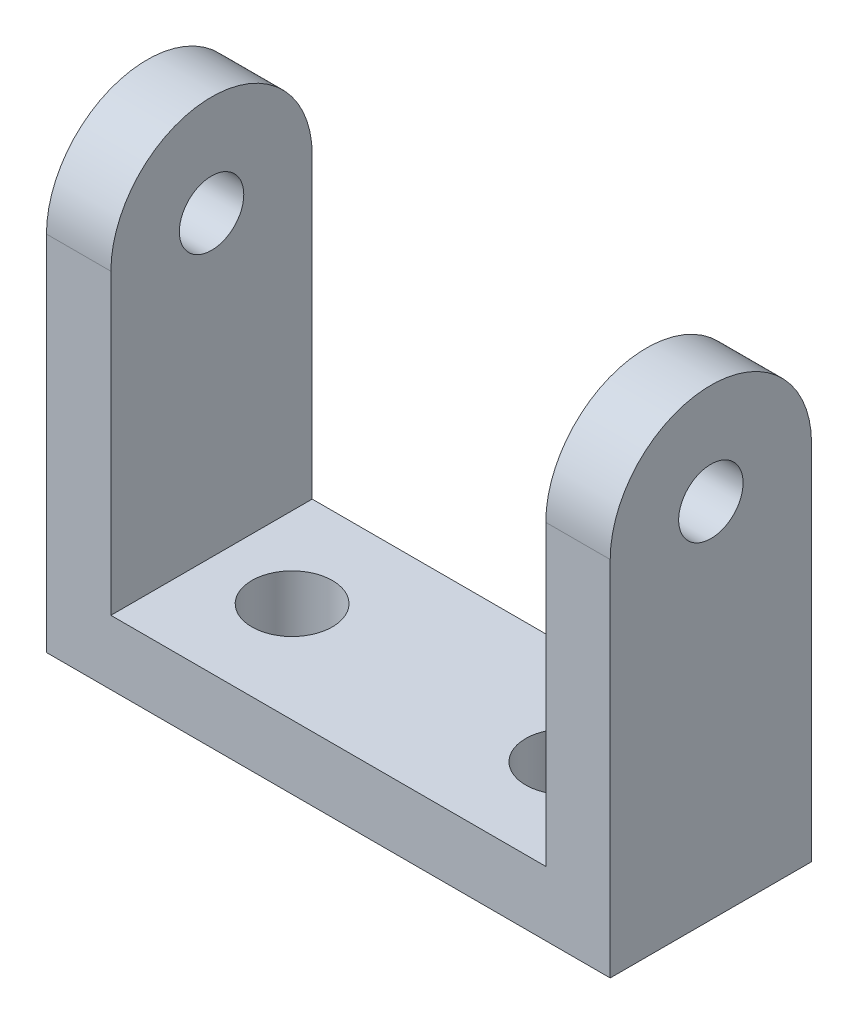
SolidWorks part; units mm, degrees
ref_plane "Piano frontale" through (0, 0, 0) normal (0, 0, 1) x (1, 0, 0)
ref_plane "Piano superiore" through (0, 0, 0) normal (0, 1, 0) x (1, 0, 0)
ref_plane "Piano destro" through (0, 0, 0) normal (1, 0, 0) x (0, 0, -1)
sketch "Schizzo1" plane through (0, 0, 0) normal (0, 0, 1) x (1, 0, 0)
  line L0 (-35, 0) -> (35, 0)
  line L1 (35, 0) -> (35, 45)
  line L2 (35, 45) -> (27, 45)
  line L3 (27, 45) -> (27, 8)
  line L4 (27, 8) -> (-27, 8)
  line L5 (-27, 8) -> (-27, 45)
  line L6 (-27, 45) -> (-35, 45)
  line L7 (-35, 45) -> (-35, 0)
  dimension "D1" = 8
  dimension "D2" = 8
  dimension "D3" = 8
  dimension "D4" = 70
  dimension "D5" = 45
  dimension "D6" = 45
extrude "Estrusione-Estrusione1" add sketch "Schizzo1" along normal mid plane 25
sketch "Schizzo2" plane through (0, 0, 0) normal (1, 0, 0) x (0, 0, -1)
  line L0 (-12.5, 45) -> (12.5, 45) construction
  circle A0 centre (0, 45) radius 12.5
  dimension "D1" = 25
extrude "Estrusione-Estrusione2" add sketch "Schizzo2" along normal blind 8 from offset 27
mirror "Specchia1" about plane through (0, 0, 0) normal (1, 0, 0) of "Estrusione-Estrusione2"
sketch "Schizzo3" plane through (0, 0, 0) normal (1, 0, 0) x (0, 0, -1)
  circle A0 centre (0, 45) radius 4
  dimension "D1" = 8
extrude "Taglio-Estrusione1" cut sketch "Schizzo3" against normal through all both and the other way through all
sketch "Schizzo4" plane through (0, 8, 0) normal (0, 1, 0) x (1, 0, 0)
  circle A0 centre (-17, 0) radius 5
  circle A1 centre (17, 0) radius 5
  point P4 (0, 0)
  point P6 (-17.2394, 0)
  dimension "D3" = 10
  dimension "D1" = 34
  dimension "D2" = 17
extrude "Taglio-Estrusione2" cut sketch "Schizzo4" against normal through all
